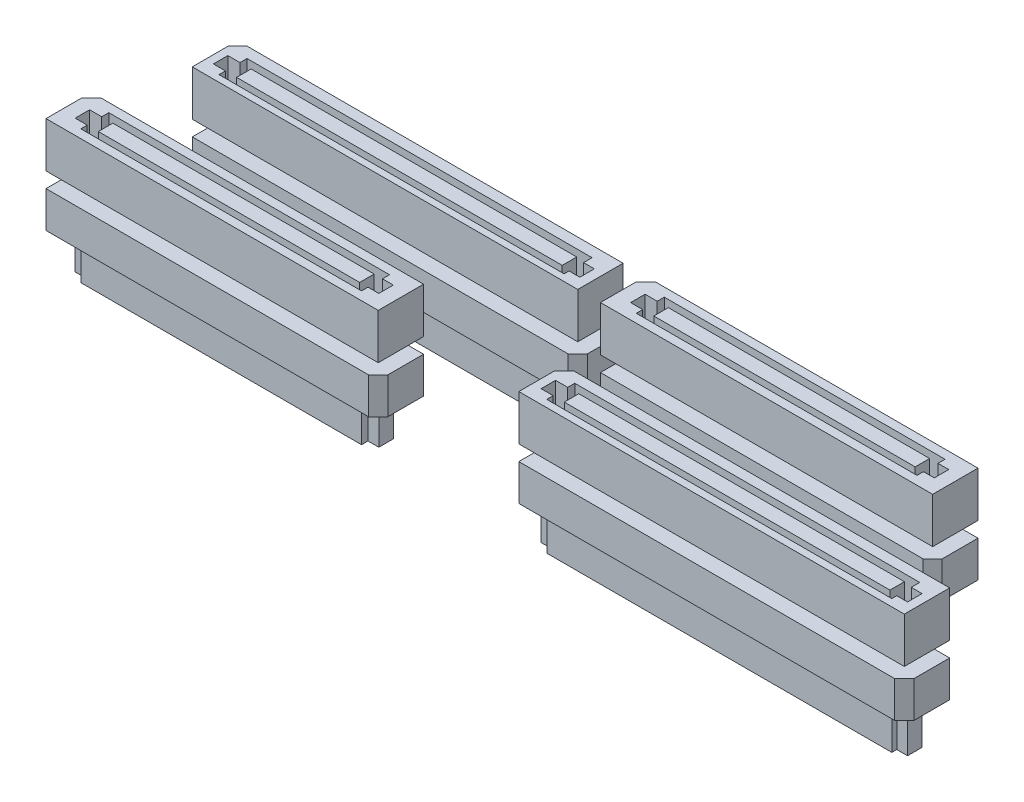
SolidWorks part; units mm, degrees
ref_plane "Front Plane" through (0, 0, 0) normal (0, 0, 1) x (1, 0, 0)
ref_plane "Top Plane" through (0, 0, 0) normal (0, 1, 0) x (1, 0, 0)
ref_plane "Right Plane" through (0, 0, 0) normal (1, 0, 0) x (0, 0, -1)
ref_plane "Plane1" through (0, -1.6866, 0) normal (0, 1, 0) x (1, 0, 0)
ref_plane "center-of-slot" through (0, -0.8433, 0) normal (0, 1, 0) x (1, 0, 0)
sketch "Sketch1" plane through (0, 0, 0) normal (0, 1, 0) x (1, 0, 0)
  line L0 (55.811, 9.5) -> (97.25, 9.5)
  line L1 (3.686, 9.5) -> (39.25, 9.5)
  line L2 (2.625, 8.439) -> (2.625, 4.5)
  line L3 (2.625, 4.5) -> (39.25, 4.5) construction
  line L4 (39.25, 9.5) -> (39.25, 4.5) construction
  line L5 (0, 0) -> (100, 0) construction
  line L6 (0, 0) -> (0, 75) construction
  line L7 (0, 75) -> (100, 75) construction
  line L8 (100, 0) -> (100, 75) construction
  line L9 (54.75, 8.439) -> (54.75, 4.5)
  line L10 (54.75, 4.5) -> (97.25, 4.5) construction
  line L11 (97.25, 9.5) -> (97.25, 4.5) construction
  line L12 (51.811, 22.5) -> (87.375, 22.5)
  line L13 (6.811, 22.5) -> (48.25, 22.5)
  line L14 (5.75, 21.439) -> (5.75, 17.5)
  line L15 (5.75, 17.5) -> (48.25, 17.5) construction
  line L16 (48.25, 22.5) -> (48.25, 17.5) construction
  line L17 (50.75, 21.439) -> (50.75, 17.5)
  line L18 (50.75, 17.5) -> (87.375, 17.5) construction
  line L19 (87.375, 22.5) -> (87.375, 17.5) construction
  line L20 (5.75, 21.439) -> (6.811, 22.5)
  line L21 (50.75, 21.439) -> (51.811, 22.5)
  line L22 (54.75, 8.439) -> (55.811, 9.5)
  line L23 (2.625, 8.439) -> (3.686, 9.5)
  line L24 (2.625, 4.5) -> (38.195, 4.5)
  line L25 (38.195, 4.5) -> (39.25, 5.555) construction
  line L26 (39.25, 5.555) -> (39.25, 9.5)
  line L27 (50.75, 17.5) -> (86.32, 17.5)
  line L28 (86.32, 17.5) -> (87.375, 18.555) construction
  line L29 (87.375, 18.555) -> (87.375, 22.5)
  line L30 (54.75, 4.5) -> (96.19, 4.5)
  line L31 (96.19, 4.5) -> (97.25, 5.56) construction
  line L32 (97.25, 5.56) -> (97.25, 9.5)
  line L33 (5.75, 17.5) -> (47.19, 17.5)
  line L34 (47.19, 17.5) -> (48.25, 18.56) construction
  line L35 (48.25, 18.56) -> (48.25, 22.5)
  line L36 (47.19, 17.5) -> (48.25, 17.5)
  line L37 (48.25, 17.5) -> (48.25, 18.56)
  line L38 (38.195, 4.5) -> (39.25, 4.5)
  line L39 (39.25, 4.5) -> (39.25, 5.555)
  line L40 (86.32, 17.5) -> (87.375, 17.5)
  line L41 (87.375, 17.5) -> (87.375, 18.555)
  line L42 (96.19, 4.5) -> (97.25, 4.5)
  line L43 (97.25, 4.5) -> (97.25, 5.56)
  point P0 (2.625, 9.5)
  point P9 (54.75, 9.5)
  point P13 (5.75, 22.5)
  point P17 (50.75, 22.5)
extrude "SV" add sketch "Sketch1" along normal blind 5
sketch "Sketch3" plane through (0, 5, 0) normal (0, 1, 0) x (1, 0, 0)
  line L0 (4.1893, 7.7457) -> (5.5243, 7.7457)
  line L1 (4.1893, 8.5242) -> (37.667, 8.5242) construction
  line L2 (4.1893, 8.5242) -> (4.1893, 5.4386) construction
  line L3 (4.1893, 5.4386) -> (37.667, 5.4386) construction
  line L4 (37.667, 8.5242) -> (37.667, 5.4386) construction
  line L5 (5.5243, 7.7457) -> (5.5243, 8.5242)
  line L6 (5.5243, 8.5242) -> (36.4757, 8.5242)
  line L7 (36.4757, 8.5242) -> (36.4757, 7.7457)
  line L8 (36.4757, 7.7457) -> (37.667, 7.7457)
  line L9 (37.667, 7.7457) -> (37.667, 6.1479)
  line L10 (37.667, 6.1479) -> (36.4757, 6.1479)
  line L11 (36.4757, 6.1479) -> (36.4757, 5.4386)
  line L12 (36.4757, 5.4386) -> (5.5243, 5.4386)
  line L13 (5.5243, 5.4386) -> (5.5243, 6.1479)
  line L14 (5.5243, 6.1479) -> (4.1893, 6.1479)
  line L15 (4.1893, 6.1479) -> (4.1893, 7.7457)
  line L16 (52.4211, 20.7536) -> (53.7561, 20.7536)
  line L17 (6.7471, 7.7457) -> (35.5588, 7.7457)
  line L18 (6.7471, 7.7457) -> (6.7471, 6.1479)
  line L19 (6.7471, 6.1479) -> (35.5588, 6.1479)
  line L20 (35.5588, 7.7457) -> (35.5588, 6.1479)
  line L21 (52.4211, 21.532) -> (85.8988, 21.532) construction
  line L22 (52.4211, 21.532) -> (52.4211, 18.4464) construction
  line L23 (52.4211, 18.4464) -> (85.8988, 18.4464) construction
  line L24 (85.8988, 21.532) -> (85.8988, 18.4464) construction
  line L25 (53.7561, 20.7536) -> (53.7561, 21.532)
  line L26 (53.7561, 21.532) -> (84.7075, 21.532)
  line L27 (84.7075, 21.532) -> (84.7075, 20.7536)
  line L28 (84.7075, 20.7536) -> (85.8988, 20.7536)
  line L29 (85.8988, 20.7536) -> (85.8988, 19.1558)
  line L30 (85.8988, 19.1558) -> (84.7075, 19.1558)
  line L31 (84.7075, 19.1558) -> (84.7075, 18.4464)
  line L32 (84.7075, 18.4464) -> (53.7561, 18.4464)
  line L33 (53.7561, 18.4464) -> (53.7561, 19.1558)
  line L34 (53.7561, 19.1558) -> (52.4211, 19.1558)
  line L35 (52.4211, 19.1558) -> (52.4211, 20.7536)
  line L36 (54.9789, 20.7536) -> (83.7906, 20.7536)
  line L37 (54.9789, 20.7536) -> (54.9789, 19.1558)
  line L38 (54.9789, 19.1558) -> (83.7906, 19.1558)
  line L39 (83.7906, 20.7536) -> (83.7906, 19.1558)
  line L40 (55.7059, 7.599) -> (57.0409, 7.599)
  line L41 (55.7059, 8.3775) -> (96.2696, 8.3775) construction
  line L42 (55.7059, 8.3775) -> (55.7059, 5.2919) construction
  line L43 (55.7059, 5.2919) -> (96.2696, 5.2919) construction
  line L44 (96.2696, 8.3775) -> (96.2696, 5.2919) construction
  line L45 (57.0409, 7.599) -> (57.0409, 8.3775)
  line L46 (57.0409, 8.3775) -> (95.0783, 8.3775)
  line L47 (95.0783, 8.3775) -> (95.0783, 7.4377)
  line L48 (95.0783, 7.4377) -> (96.2696, 7.4377)
  line L49 (96.2696, 7.4377) -> (96.2696, 5.8399)
  line L50 (96.2696, 5.8399) -> (95.0783, 5.8399)
  line L51 (95.0783, 5.8399) -> (95.0783, 5.2919)
  line L52 (95.0783, 5.2919) -> (57.0409, 5.2919)
  line L53 (57.0409, 5.2919) -> (57.0409, 6.0012)
  line L54 (57.0409, 6.0012) -> (55.7059, 6.0012)
  line L55 (55.7059, 6.0012) -> (55.7059, 7.599)
  line L56 (58.2637, 7.599) -> (94.1615, 7.599)
  line L57 (58.2637, 7.599) -> (58.2637, 6.0012)
  line L58 (58.2637, 6.0012) -> (94.1615, 6.0012)
  line L59 (94.1615, 7.599) -> (94.1615, 6.0012)
  line L60 (6.6366, 20.5397) -> (7.9716, 20.5397)
  line L61 (6.6366, 21.3182) -> (47.2003, 21.3182) construction
  line L62 (6.6366, 21.3182) -> (6.6366, 18.2325) construction
  line L63 (6.6366, 18.2325) -> (47.2003, 18.2325) construction
  line L64 (47.2003, 21.3182) -> (47.2003, 18.2325) construction
  line L65 (7.9716, 20.5397) -> (7.9716, 21.3182)
  line L66 (7.9716, 21.3182) -> (46.009, 21.3182)
  line L67 (46.009, 21.3182) -> (46.009, 20.3784)
  line L68 (46.009, 20.3784) -> (47.2003, 20.3784)
  line L69 (47.2003, 20.3784) -> (47.2003, 18.7806)
  line L70 (47.2003, 18.7806) -> (46.009, 18.7806)
  line L71 (46.009, 18.7806) -> (46.009, 18.2325)
  line L72 (46.009, 18.2325) -> (7.9716, 18.2325)
  line L73 (7.9716, 18.2325) -> (7.9716, 18.9419)
  line L74 (7.9716, 18.9419) -> (6.6366, 18.9419)
  line L75 (6.6366, 18.9419) -> (6.6366, 20.5397)
  line L76 (9.1944, 20.5397) -> (45.0922, 20.5397)
  line L77 (9.1944, 20.5397) -> (9.1944, 18.9419)
  line L78 (9.1944, 18.9419) -> (45.0922, 18.9419)
  line L79 (45.0922, 20.5397) -> (45.0922, 18.9419)
extrude "Cut-Extrude1" cut sketch "Sketch3" against normal blind 4
sketch "Sketch6" plane through (0, -1.6866, 0) normal (0, 1, 0) x (1, 0, 0)
  line L0 (2.625, 4.5) -> (2.625, 9.5) construction
  line L1 (5.75, 22.5) -> (48.25, 22.5) construction
  line L2 (5.75, 22.5) -> (5.75, 17.5) construction
  line L3 (5.75, 17.5) -> (48.25, 17.5) construction
  line L4 (48.25, 22.5) -> (48.25, 17.5) construction
  line L5 (50.75, 22.5) -> (87.375, 22.5) construction
  line L6 (50.75, 22.5) -> (50.75, 17.5) construction
  line L7 (50.75, 17.5) -> (87.375, 17.5) construction
  line L8 (87.375, 22.5) -> (87.375, 17.5) construction
  line L9 (97.25, 9.5) -> (54.75, 9.5) construction
  line L10 (97.25, 9.5) -> (97.25, 4.5) construction
  line L11 (97.25, 4.5) -> (54.75, 4.5) construction
  line L12 (54.75, 9.5) -> (54.75, 4.5) construction
  line L13 (39.25, 9.5) -> (2.625, 9.5) construction
  line L14 (39.25, 9.5) -> (39.25, 4.5) construction
  line L15 (39.25, 4.5) -> (2.625, 4.5) construction
  line L16 (2.625, 9.5) -> (2.625, 4.5) construction
  line L17 (2.625, 4.5) -> (38.195, 4.5)
  line L18 (2.625, 9.5) -> (39.25, 9.5) construction
  line L19 (48.25, 18.5619) -> (47.1881, 17.5)
  line L20 (39.25, 5.555) -> (39.25, 9.5)
  line L21 (48.25, 18.5619) -> (48.25, 22.5)
  line L22 (47.1881, 17.5) -> (5.75, 17.5)
  line L23 (39.25, 5.555) -> (38.195, 4.5)
  line L24 (54.75, 4.5) -> (96.19, 4.5)
  line L25 (96.19, 4.5) -> (97.25, 5.56)
  line L26 (97.25, 5.56) -> (97.25, 9.5)
  line L27 (50.75, 17.5) -> (86.32, 17.5)
  line L28 (86.32, 17.5) -> (87.375, 18.555)
  line L29 (87.375, 18.555) -> (87.375, 22.5)
  line L30 (2.625, 4.5) -> (2.625, 8.44)
  line L31 (2.625, 8.44) -> (3.685, 9.5) construction
  line L32 (3.685, 9.5) -> (39.25, 9.5)
  line L33 (5.75, 17.5) -> (5.75, 21.44)
  line L34 (5.75, 21.44) -> (6.81, 22.5) construction
  line L35 (6.81, 22.5) -> (48.25, 22.5)
  line L36 (54.75, 4.5) -> (54.75, 8.44)
  line L37 (54.75, 8.44) -> (55.81, 9.5) construction
  line L38 (55.81, 9.5) -> (97.25, 9.5)
  line L39 (87.375, 22.5) -> (51.805, 22.5)
  line L40 (51.805, 22.5) -> (50.75, 21.445) construction
  line L41 (50.75, 21.445) -> (50.75, 17.5)
  line L42 (3.685, 9.5) -> (2.625, 9.5)
  line L43 (2.625, 9.5) -> (2.625, 8.44)
  line L44 (6.81, 22.5) -> (5.75, 22.5)
  line L45 (5.75, 22.5) -> (5.75, 21.44)
  line L46 (50.75, 21.445) -> (50.75, 22.5)
  line L47 (50.75, 22.5) -> (51.805, 22.5)
  line L48 (54.75, 8.44) -> (54.75, 9.5)
  line L49 (54.75, 9.5) -> (55.81, 9.5)
  point P0 (5.75, 22.5)
  point P6 (50.75, 22.5)
  point P15 (54.75, 9.5)
extrude "SV4(a)" add sketch "Sketch6" against normal blind 4 separate body
sketch "Sketch7" plane through (0, -5.6866, 0) normal (0, -1, 0) x (1, 0, 0)
  line L0 (7.9716, -21.3182) -> (7.9716, -20.5397)
  line L1 (7.9716, -20.5397) -> (6.6366, -20.5397)
  line L2 (6.6366, -20.5397) -> (6.6366, -18.9419)
  line L3 (6.6366, -18.9419) -> (7.9716, -18.9419)
  line L4 (7.9716, -18.9419) -> (7.9716, -18.2325)
  line L6 (7.9716, -18.2325) -> (46.009, -18.2325)
  line L7 (46.009, -18.2325) -> (46.009, -18.7806)
  line L8 (46.009, -18.7806) -> (47.2003, -18.7806)
  line L9 (47.2003, -18.7806) -> (47.2003, -20.3784)
  line L10 (47.2003, -20.3784) -> (46.009, -20.3784)
  line L11 (46.009, -20.3784) -> (46.009, -21.3182)
  line L12 (46.009, -21.3182) -> (7.9716, -21.3182)
  line L13 (53.7561, -21.532) -> (84.7075, -21.532)
  line L14 (9.1944, -20.5397) -> (45.0922, -20.5397)
  line L15 (9.1944, -20.5397) -> (9.1944, -18.9419)
  line L16 (9.1944, -18.9419) -> (45.0922, -18.9419)
  line L17 (45.0922, -20.5397) -> (45.0922, -18.9419)
  line L18 (54.9789, -20.7536) -> (83.7906, -20.7536)
  line L19 (54.9789, -20.7536) -> (54.9789, -19.1558)
  line L20 (54.9789, -19.1558) -> (83.7906, -19.1558)
  line L21 (83.7906, -20.7536) -> (83.7906, -19.1558)
  line L22 (94.1615, -7.599) -> (58.2637, -7.599)
  line L23 (94.1615, -7.599) -> (94.1615, -6.0012)
  line L24 (94.1615, -6.0012) -> (58.2637, -6.0012)
  line L25 (58.2637, -7.599) -> (58.2637, -6.0012)
  line L26 (35.5588, -7.7457) -> (6.7471, -7.7457)
  line L27 (35.5588, -7.7457) -> (35.5588, -6.1479)
  line L28 (35.5588, -6.1479) -> (6.7471, -6.1479)
  line L29 (6.7471, -7.7457) -> (6.7471, -6.1479)
  line L30 (84.7075, -21.532) -> (84.7075, -20.7536)
  line L31 (84.7075, -20.7536) -> (85.8988, -20.7536)
  line L32 (85.8988, -20.7536) -> (85.8988, -19.1558)
  line L33 (85.8988, -19.1558) -> (84.7075, -19.1558)
  line L34 (84.7075, -19.1558) -> (84.7075, -18.4464)
  line L35 (84.7075, -18.4464) -> (53.7561, -18.4464)
  line L36 (53.7561, -18.4464) -> (53.7561, -19.1558)
  line L37 (53.7561, -19.1558) -> (52.4211, -19.1558)
  line L38 (52.4211, -19.1558) -> (52.4211, -20.7536)
  line L39 (52.4211, -20.7536) -> (53.7561, -20.7536)
  line L40 (53.7561, -20.7536) -> (53.7561, -21.532)
  line L41 (57.0409, -8.3775) -> (57.0409, -7.599)
  line L42 (57.0409, -7.599) -> (55.7059, -7.599)
  line L43 (55.7059, -7.599) -> (55.7059, -6.0012)
  line L44 (55.7059, -6.0012) -> (57.0409, -6.0012)
  line L45 (57.0409, -6.0012) -> (57.0409, -5.2919)
  line L46 (57.0409, -5.2919) -> (95.0783, -5.2919)
  line L47 (95.0783, -5.2919) -> (95.0783, -5.8399)
  line L48 (95.0783, -5.8399) -> (96.2696, -5.8399)
  line L49 (96.2696, -5.8399) -> (96.2696, -7.4377)
  line L50 (96.2696, -7.4377) -> (95.0783, -7.4377)
  line L51 (95.0783, -7.4377) -> (95.0783, -8.3775)
  line L52 (95.0783, -8.3775) -> (57.0409, -8.3775)
  line L53 (4.1893, -6.1479) -> (5.5243, -6.1479)
  line L54 (5.5243, -6.1479) -> (5.5243, -5.4386)
  line L55 (5.5243, -5.4386) -> (36.4757, -5.4386)
  line L56 (36.4757, -5.4386) -> (36.4757, -6.1479)
  line L57 (36.4757, -6.1479) -> (37.667, -6.1479)
  line L58 (37.667, -6.1479) -> (37.667, -7.7457)
  line L59 (37.667, -7.7457) -> (36.4757, -7.7457)
  line L60 (36.4757, -7.7457) -> (36.4757, -8.5242)
  line L61 (36.4757, -8.5242) -> (5.5243, -8.5242)
  line L62 (5.5243, -8.5242) -> (5.5243, -7.7457)
  line L63 (5.5243, -7.7457) -> (4.1893, -7.7457)
  line L64 (4.1893, -7.7457) -> (4.1893, -6.1479)
extrude "SV4(b)" add sketch "Sketch7" along normal blind 4
